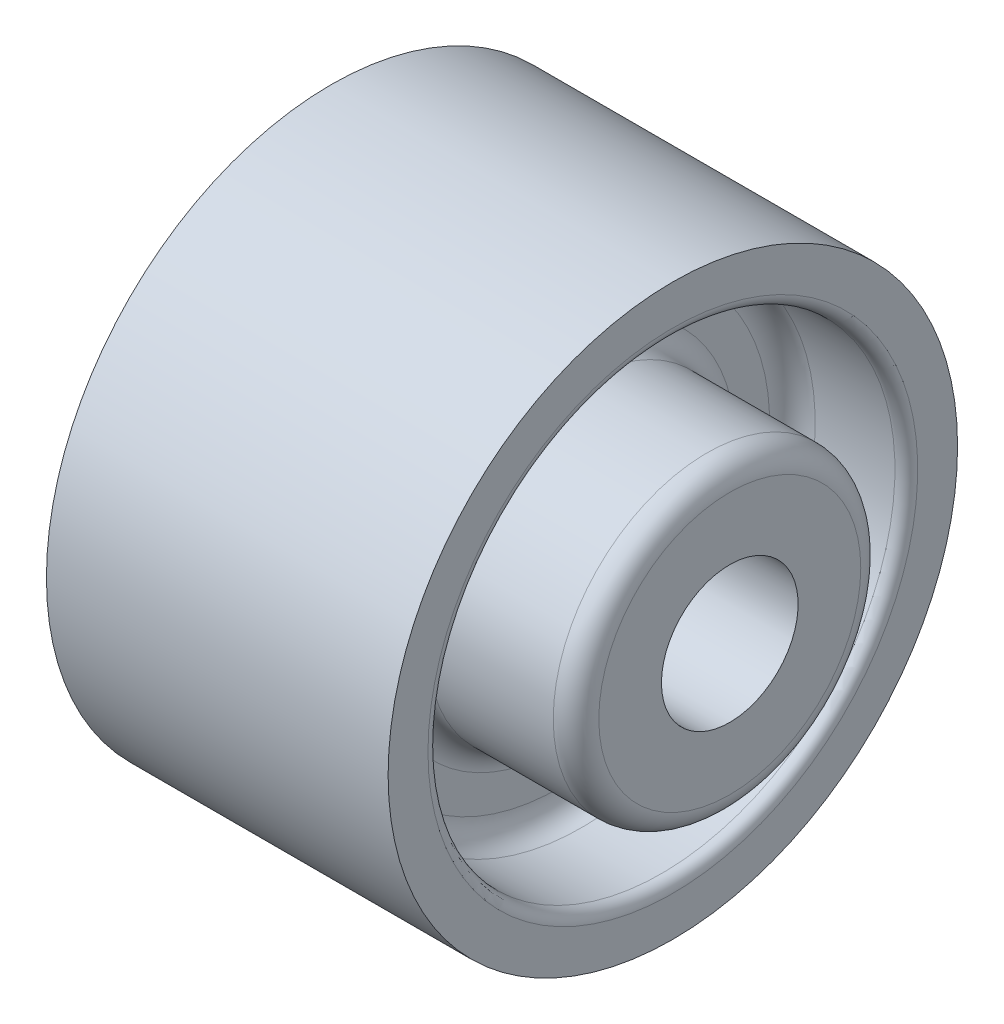
SolidWorks part; units mm, degrees
material "Полиуретан"
ref_plane "Спереди" through (0, 0, 0) normal (0, 0, 1) x (1, 0, 0)
ref_plane "Сверху" through (0, 0, 0) normal (0, 1, 0) x (1, 0, 0)
ref_plane "Справа" through (0, 0, 0) normal (1, 0, 0) x (0, 0, -1)
sketch "Эскиз1" plane through (0, 0, 0) normal (0, 0, 1) x (1, 0, 0)
  line L0 (-52.3821, 0) -> (52.3821, 0) construction
  line L1 (0, -118.3275) -> (0, 118.3275) construction
  line L2 (-20, 6) -> (20, 6)
  line L3 (-15, -32.5) -> (15, -32.5) construction
  line L4 (-15, -32.5) -> (-15, 32.5) construction
  line L5 (-15, 32.5) -> (15, 32.5) construction
  line L6 (15, -32.5) -> (15, 32.5) construction
  line L7 (-15, -32.5) -> (15, 32.5) construction
  line L8 (-15, 32.5) -> (15, -32.5) construction
  line L9 (15, -13.5) -> (-15, -13.5) construction
  line L10 (15, -13.5) -> (15, 13.5) construction
  line L11 (15, 13.5) -> (-15, 13.5) construction
  line L12 (-15, -13.5) -> (-15, 13.5) construction
  line L13 (15, -13.5) -> (-15, 13.5) construction
  line L14 (15, 13.5) -> (-15, -13.5) construction
  line L15 (-5, -32.5) -> (5, -32.5) construction
  line L16 (-5, -32.5) -> (-5, 32.5) construction
  line L17 (-5, 32.5) -> (5, 32.5) construction
  line L18 (5, -32.5) -> (5, 32.5) construction
  line L19 (-5, -32.5) -> (5, 32.5) construction
  line L20 (-5, 32.5) -> (5, -32.5) construction
  line L21 (-15, -4) -> (15, -4) construction
  line L22 (-15, -4) -> (-15, 4) construction
  line L23 (-15, 4) -> (15, 4) construction
  line L24 (15, -4) -> (15, 4) construction
  line L25 (-15, -4) -> (15, 4) construction
  line L26 (-15, 4) -> (15, -4) construction
  line L27 (15, -25) -> (-15, -25) construction
  line L28 (15, -25) -> (15, 25) construction
  line L29 (15, 25) -> (-15, 25) construction
  line L30 (-15, -25) -> (-15, 25) construction
  line L31 (15, -25) -> (-15, 25) construction
  line L32 (15, 25) -> (-15, -25) construction
  line L33 (15, -29.5) -> (-15, -29.5) construction
  line L34 (15, -29.5) -> (15, 29.5) construction
  line L35 (15, 29.5) -> (-15, 29.5) construction
  line L36 (-15, -29.5) -> (-15, 29.5) construction
  line L37 (15, -29.5) -> (-15, 29.5) construction
  line L38 (15, 29.5) -> (-15, -29.5) construction
  line L39 (20, -6) -> (-20, -6) construction
  line L40 (20, -6) -> (20, 6) construction
  line L41 (20, 6) -> (-20, 6) construction
  line L42 (-20, -6) -> (-20, 6) construction
  line L43 (20, -6) -> (-20, 6) construction
  line L44 (20, 6) -> (-20, -6) construction
  line L45 (-15, 25) -> (15, 25)
  line L46 (20, 6) -> (20, 11.5)
  line L47 (18, 13.5) -> (7, 13.5)
  line L48 (-15, 25) -> (-15, 21.5)
  line L49 (-15, -20.5) -> (15, -20.5) construction
  line L50 (-7.9098, 13.5) -> (-18, 13.5)
  line L51 (-20, 11.5) -> (-20, 6)
  line L52 (-15, -20.5) -> (-15, 20.5) construction
  line L53 (-15, 20.5) -> (15, 20.5) construction
  line L54 (15, -20.5) -> (15, 20.5) construction
  line L55 (-15, -20.5) -> (15, 20.5) construction
  line L56 (-15, 20.5) -> (15, -20.5) construction
  line L57 (-14, 20.5) -> (-7.3823, 20.5)
  line L58 (-5.4125, 18.1537) -> (-5.94, 15.1537)
  line L59 (5, 15.5) -> (5, 18.5)
  line L60 (7, 20.5) -> (14, 20.5)
  line L61 (15, 21.5) -> (15, 25)
  arc A0 (5, 18.5) -> (7, 20.5) centre (7, 18.5) cw
  arc A1 (-7.3823, 20.5) -> (-5.4125, 18.1537) centre (-7.3823, 18.5) cw
  arc A2 (-5.94, 15.1537) -> (-7.9098, 13.5) centre (-7.9098, 15.5) cw
  arc A3 (7, 13.5) -> (5, 15.5) centre (7, 15.5) cw
  arc A4 (20, 11.5) -> (18, 13.5) centre (18, 11.5) ccw
  arc A5 (-18, 13.5) -> (-20, 11.5) centre (-18, 11.5) ccw
  arc A6 (14, 20.5) -> (15, 21.5) centre (14, 21.5) ccw
  arc A7 (-15, 21.5) -> (-14, 20.5) centre (-14, 21.5) ccw
  point P0 (0, 0)
  point P4 (0, 0)
  point P7 (0, 0)
  point P12 (0, 0)
  point P17 (0, 0)
  point P22 (0, 0)
  point P27 (0, 0)
  point P32 (0, 0)
  point P37 (0, 0)
  point P45 (0, 0)
  point P55 (5, 20.5)
  point P58 (-5, 20.5)
  point P61 (-6.2308, 13.5)
  point P64 (5, 13.5)
  dimension "D8" = 4.5
  dimension "D9" = 2
  dimension "D10" = 1
  dimension "D1" = 65
  dimension "D2" = 30
  dimension "D3" = 27
  dimension "D4" = 40
  dimension "D5" = 8
  dimension "D6" = 50
  dimension "D7" = 59
revolve "Повернуть1" add sketch "Эскиз1" angle 360 about L0
